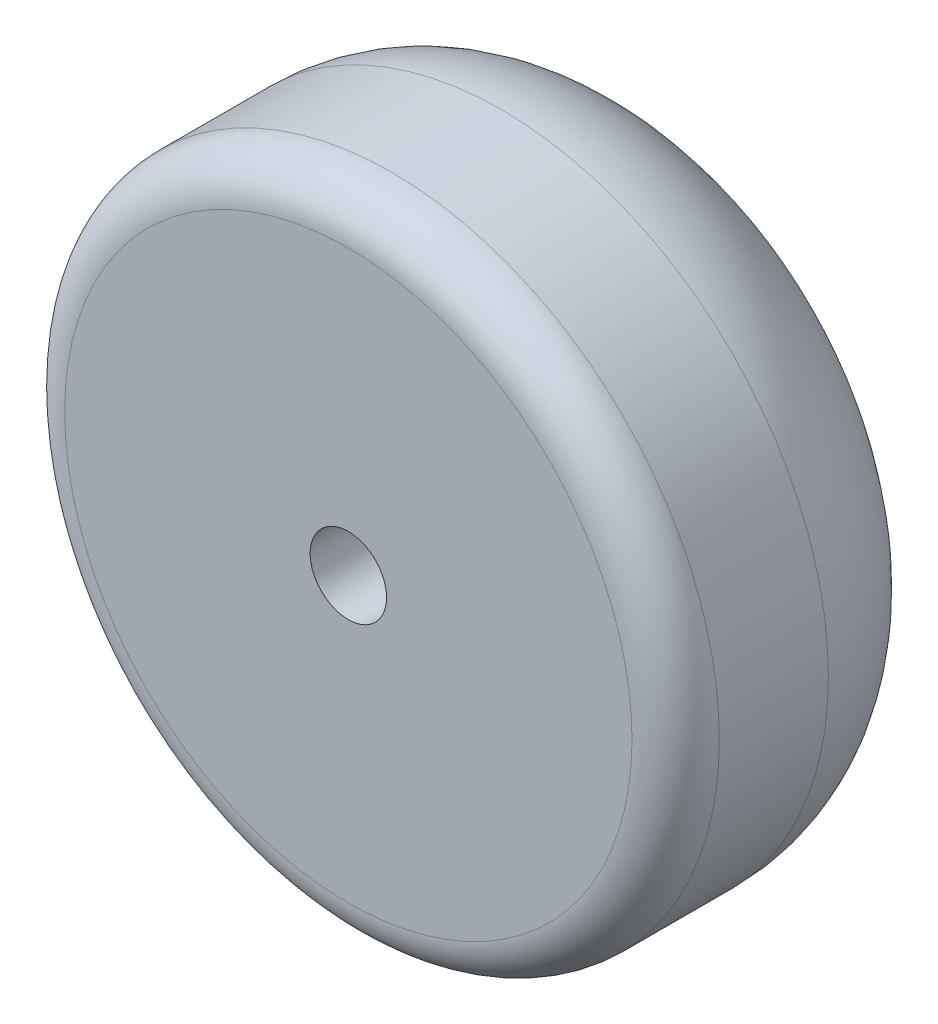
SolidWorks part; units mm, degrees
ref_plane "Спереди" through (0, 0, 0) normal (0, 0, 1) x (1, 0, 0)
ref_plane "Сверху" through (0, 0, 0) normal (0, 1, 0) x (1, 0, 0)
ref_plane "Справа" through (0, 0, 0) normal (1, 0, 0) x (0, 0, -1)
sketch "Эскиз1" plane through (0, 0, 0) normal (0, 0, 1) x (1, 0, 0)
  circle A0 centre (0, 0) radius 1.75
  circle A1 centre (0, 0) radius 15
  dimension "D1" = 3.5
  dimension "D2" = 30
extrude "Бобышка-Вытянуть1" add sketch "Эскиз1" along normal blind 14
sketch "Эскиз2" plane through (0, 0, 14) normal (0, 0, 1) x (1, 0, 0)
  circle A0 centre (0, 0) radius 5.15
  dimension "D1" = 10.3
extrude "Вырез-Вытянуть1" [suppressed] cut sketch "Эскиз2" against normal blind 4
fillet "Скругление1" radius 2 1 edges at (15, 0, 14)
fillet "Скругление2" radius 7 1 edges at (15, 0, 0)
